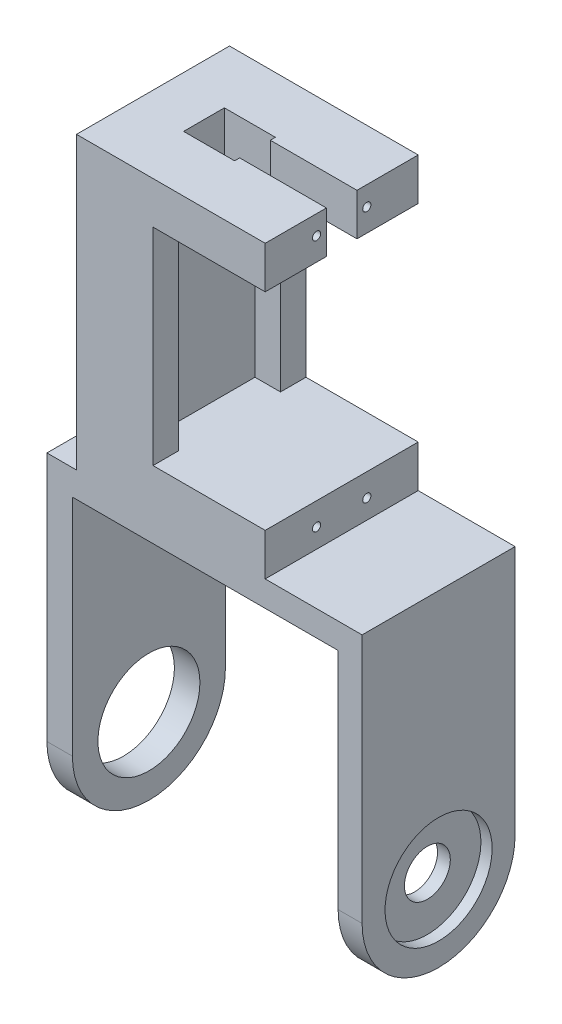
SolidWorks part; units mm, degrees
other "Marquage1"
sketch "Esquisse9" plane through (30.25, -27, 30) normal (0.9363, -0.2766, 0.2166) x (0.221, -0.0157, -0.9752)
sketch "Esquisse33" plane through (30.75, -32, 30) normal (0.9363, -0.2766, 0.2166) x (0.221, -0.0157, -0.9752)
ref_plane "Plan de face" through (0, 0, 0) normal (0, 0, 1) x (1, 0, 0)
ref_plane "Plan de dessus" through (0, 0, 0) normal (0, 1, 0) x (1, 0, 0)
ref_plane "Plan de droite" through (0, 0, 0) normal (1, 0, 0) x (0, 0, -1)
sketch "Esquisse1" plane through (0, 0, 0) normal (0, 0, 1) x (1, 0, 0)
  line L1 (-30.25, 32) -> (30.25, 32)
  line L2 (-30.25, 32) -> (-30.25, -32)
  line L3 (-30.25, -32) -> (30.25, -32)
  line L4 (30.25, 32) -> (30.25, -32)
  line L5 (-30.25, 32) -> (30.25, -32) construction
  line L6 (-30.25, -32) -> (30.25, 32) construction
  point P0 (0, 0)
  dimension "D1" = 60.5
  dimension "D2" = 64
extrude "Boss.-Extru.1" add sketch "Esquisse1" along normal blind 30
sketch "Esquisse2" plane through (30.25, 0, 0) normal (1, 0, 0) x (0, 0, -1)
  line L0 (-15, 32) -> (-15, -32) construction
  line L1 (-30, 32) -> (0, 32) construction
  line L2 (-30, -32) -> (0, -32) construction
  circle A0 centre (-15, -17) radius 4.5
  point P8 (-15, -17)
  dimension "D1" = 15
  dimension "D2" = 9
extrude "Enlèv. mat.-Extru.1" cut sketch "Esquisse2" against normal blind 32
sketch "Esquisse4" plane through (0, 0, 30) normal (0, 0, 1) x (1, 0, 0)
  line L0 (0, 0) -> (0, -11.7818) construction
  line L1 (-26.05, -56.5577) -> (26.05, -56.5577)
  line L2 (-26.05, -56.5577) -> (-26.05, 27)
  line L3 (-26.05, 27) -> (26.05, 27)
  line L4 (26.05, -56.5577) -> (26.05, 27)
  line L5 (30.25, 32) -> (-30.25, 32) construction
  line L6 (-30.25, 32) -> (-30.25, -32) construction
  dimension "D1" = 52.1
  dimension "D2" = 5
  dimension "D3" = 4.2
extrude "Enlèv. mat.-Extru.2" cut sketch "Esquisse4" against normal up to surface (30 mm away) up to face at (0, 0, 0)
sketch "Esquisse5" plane through (30.25, 0, 0) normal (1, 0, 0) x (0, 0, -1)
  circle A0 centre (-15, -17) radius 10.5
  dimension "D1" = 21
extrude "Enlèv. mat.-Extru.3" cut sketch "Esquisse5" against normal offset from surface (1.7 mm away) 2.5 up to face at (26.05, -12.5, 15)
sketch "Esquisse6" plane through (-26.05, 0, 0) normal (1, 0, 0) x (0, 0, -1)
  circle A0 centre (-15, -17) radius 10
extrude "Enlèv. mat.-Extru.4" cut sketch "Esquisse6" against normal up to surface (4.2 mm away) up to face at (-30.25, 0, 15)
sketch "Esquisse7" plane through (0, 0, 30) normal (0, 0, 1) x (1, 0, 0)
  line L0 (0, 0) -> (0, 32.5445) construction
  line L2 (-30.25, 32) -> (16.75, 32)
  line L3 (-30.25, 32) -> (-30.25, 89)
  line L4 (-30.25, 89) -> (16.75, 89)
  line L5 (16.75, 32) -> (16.75, 89)
  dimension "D1" = 57
  dimension "D2" = 47
extrude "Boss.-Extru.2" add sketch "Esquisse7" against normal up to surface (30 mm away) up to face at (0, -1.25, 0)
sketch "Esquisse8" plane through (0, 0, 30) normal (0, 0, 1) x (1, 0, 0)
  line L0 (-15.25, 90.392) -> (-15.25, 19.4965) construction
  line L1 (-30.25, 89) -> (-30.25, -32) construction
  line L2 (16.75, 60.5) -> (-55.9253, 60.5) construction
  line L3 (16.75, 32) -> (16.75, 89) construction
  line L4 (30.25, 32) -> (16.75, 32) construction
  line L6 (-15.25, 80.75) -> (11.75, 80.75)
  line L7 (-15.25, 80.75) -> (-15.25, 40.25)
  line L8 (-15.25, 40.25) -> (11.75, 40.25)
  line L10 (11.75, 40.25) -> (11.75, 32)
  line L11 (11.75, 98.5564) -> (21.75, 98.5564)
  line L12 (11.75, 98.5564) -> (11.75, 80.75)
  line L13 (11.75, 32) -> (21.75, 32)
  line L14 (21.75, 98.5564) -> (21.75, 32)
  dimension "D1" = 15
  dimension "D2" = 28.5
  dimension "D3" = 28.5
  dimension "D4" = 40.5
  dimension "D5" = 27
  dimension "D6" = 10
extrude "Enlèv. mat.-Extru.5" cut sketch "Esquisse8" against normal up to surface (30 mm away) up to face at (3.35, 16.8, 0)
sketch "Esquisse10" plane through (0, 80.75, 0) normal (0, -1, 0) x (1, 0, 0)
  line L0 (-1.75, 30) -> (-1.75, -1.0034) construction
  line L1 (-15.25, 15) -> (11.75, 15) construction
  line L2 (5.75, 0) -> (11.75, 0) construction
  line L4 (-15.25, 0) -> (11.75, 0)
  line L5 (11.75, 0) -> (11.75, 30)
  line L6 (11.75, 30) -> (-15.25, 30)
  line L7 (-15.25, 30) -> (-15.25, 0)
  line L8 (-15.25, 0) -> (-9.25, 0) construction
  line L9 (11.75, 0) -> (11.75, 30) construction
  line L10 (11.75, 30) -> (-15.25, 30) construction
  line L11 (-15.25, 30) -> (-15.25, 0) construction
  line L15 (-5.25, 11) -> (-5.25, 12)
  line L16 (-15.25, 19) -> (-5.25, 19)
  line L17 (-15.25, 19) -> (-15.25, 11)
  line L18 (-15.25, 11) -> (-5.25, 11)
  line L19 (34.75, 18) -> (34.75, 12)
  line L21 (-5.25, 19) -> (-5.25, 18)
  line L22 (-5.25, 18) -> (34.75, 18)
  line L24 (-5.25, 12) -> (34.75, 12)
  dimension "D2" = 6
  dimension "D4" = 10
  dimension "D1" = 0
extrude "Enlèv. mat.-Extru.6" cut sketch "Esquisse10" against normal up to surface (8.25 mm away) contours L17 L18 L15 L24 L19 L22 L21 L16 up to face at (-9.25, 89, 15)
sketch "Esquisse11" plane through (-15.25, 0, 0) normal (1, 0, 0) x (0, 0, -1)
  line L0 (-15, 103.0984) -> (-15, 64.9016) construction
  line L2 (0, 40.25) -> (-30, 40.25) construction
  line L3 (-30, 80.75) -> (-25, 80.75)
  line L4 (-30, 80.75) -> (-30, 40.25)
  line L5 (-30, 40.25) -> (-25, 40.25)
  line L6 (-25, 80.75) -> (-25, 40.25)
  line L7 (0, 40.25) -> (-5, 40.25)
  line L8 (-5, 80.75) -> (-5, 40.25)
  line L9 (0, 80.75) -> (-5, 80.75)
  line L10 (0, 80.75) -> (0, 40.25)
  point P3 (-15, 84)
  dimension "D1" = 5
extrude "Boss.-Extru.3" add sketch "Esquisse11" along normal blind 5
sketch "Esquisse12" plane through (11.75, 0, 0) normal (1, 0, 0) x (0, 0, -1)
  line L0 (-15, 89) -> (-15, 40.25) construction
  line L1 (-19, 89) -> (-11, 89) construction
  line L2 (0, 40.25) -> (-30, 40.25) construction
  line L3 (0, 80.75) -> (-12, 80.75) construction
  line L4 (-25, 60.5) -> (3.7732, 60.5) construction
  line L5 (-25, 40.25) -> (-25, 80.75) construction
  circle A0 centre (-19.925, 85.21) radius 0.5
  circle A1 centre (-10.075, 85.21) radius 0.5
  circle A2 centre (-10.075, 35.79) radius 0.5
  circle A3 centre (-19.925, 35.79) radius 0.5
  point P6 (-10.075, 85.21)
  point P9 (-19.925, 35.79)
  point P10 (-19.925, 85.21)
  point P15 (-10.075, 35.79)
  dimension "D3" = 1
  dimension "D1" = 4.46
  dimension "D2" = 4.925
  dimension "D4" = 4.925
  dimension "D5" = 4.46
extrude "Enlèv. mat.-Extru.7" cut sketch "Esquisse12" against normal blind 15
hole_wizard "Trou taraudé M2x0.42" positions "Esquisse3D2" profile "Esquisse14" tap size "M2x0.4" standard "Ansi Metric"
sketch3d "Esquisse3D2"
  line L0 (-3.25, 85.21, 19.925) -> (11.75, 85.21, 19.925) construction
  line L1 (-3.25, 85.21, 10.075) -> (11.75, 85.21, 10.075) construction
  line L2 (-3.25, 35.79, 10.075) -> (11.75, 35.79, 10.075) construction
  line L3 (-3.25, 35.79, 19.925) -> (11.75, 35.79, 19.925) construction
  point P0 (11.75, 85.21, 19.925)
  point P4 (11.75, 85.21, 10.075)
  point P8 (11.75, 35.79, 10.075)
  point P12 (11.75, 35.79, 19.925)
cosmetic thread "Filetage de perçage5" parameters "D1"=15, "D2"=2
cosmetic thread "Filetage de perçage6" parameters "D1"=15, "D2"=2
cosmetic thread "Filetage de perçage7" parameters "D1"=15, "D2"=2
cosmetic thread "Filetage de perçage8" parameters "D1"=15, "D2"=2
sketch "Esquisse14" plane through (11.75, 85.21, 19.925) normal (0, 1, 0) x (0, 0, -1)
  line L0 (0, 0) -> (0, 17.4807)
  line L1 (0, 17.4807) -> (0.8, 17)
  line L2 (0.8, 17) -> (0.8, 0)
  line L5 (0.8, 0) -> (0, 0)
  line L10 (0, 17.4807) -> (-0.8, 17) construction
  line L11 (0, -6.35) -> (0, 107.95) construction
  dimension "Diamètre du trou pour taraudage" = 1.6
  dimension "Profondeur du trou pour taraudage" = 17
  dimension "Angle de pointe" = 118
sketch "Esquisse15" plane through (-30.25, 0, 0) normal (-1, 0, 0) x (0, 0, 1)
  line L0 (30, -32) -> (0, -32) construction
  line L1 (40, -17) -> (30, -17)
  line L2 (0, -17) -> (-10, -17)
  arc A0 (5, -17) -> (25, -17) centre (15, -17) ccw construction
  arc A1 (0, -17) -> (30, -17) centre (15, -17) ccw
  arc A2 (-10, -17) -> (40, -17) centre (15, -17) ccw
  dimension "D1" = 20
  dimension "D2" = 50
extrude "Enlèv. mat.-Extru.8" cut sketch "Esquisse15" against normal up to surface (60.5 mm away) up to face at (30.25, -6.5, 15)
sketch "Esquisse17" plane through (-15.25, 0, 0) normal (1, 0, 0) x (0, 0, -1)
  line L0 (-15, 89) -> (-15, 40.25) construction
  line L1 (-19, 89) -> (-11, 89) construction
  line L2 (0, 40.25) -> (-30, 40.25) construction
  line L3 (-5, 70.15) -> (-34.9076, 70.15) construction
  line L4 (-5, 80.75) -> (-5, 40.25) construction
  line L5 (-25, 40.25) -> (-25, 80.75) construction
  line L6 (-5, 40.25) -> (-25, 40.25) construction
  circle A0 centre (-15, 70.15) radius 9.25
  point P14 (-15, 70.15)
  dimension "D1" = 10
  dimension "D2" = 29.9
sketch "Esquisse21" plane through (-30.25, 0, 0) normal (-1, 0, 0) x (0, 0, 1)
  circle A0 centre (15, 70.15) radius 9.25 construction
  circle A1 centre (15, 70.15) radius 9.25 construction
  circle A2 centre (15, 70.15) radius 1
  point P4 (15, 70.15)
hole_wizard "Trou taraudé M3x0.54" positions "Esquisse3D6" profile "Esquisse24" tap size "M3x0.5" standard "Ansi Metric"
sketch3d "Esquisse3D6"
  point P0 (-30.25, 70.15, 15)
sketch "Esquisse24" plane through (-30.25, 70.15, 15) normal (0, 1, 0) x (0, 0, 1)
  line L0 (0, 0) -> (0, 18.2511)
  line L1 (0, 18.2511) -> (1.25, 17.5)
  line L2 (1.25, 17.5) -> (1.25, 0)
  line L5 (1.25, 0) -> (0, 0)
  line L10 (0, 18.2511) -> (-1.25, 17.5) construction
  line L11 (0, -6.35) -> (0, 107.95) construction
  dimension "Diamètre du trou pour taraudage" = 2.5
  dimension "Profondeur du trou pour taraudage" = 17.5
  dimension "Angle de pointe" = 118
cosmetic thread "Filetage de perçage12" parameters "D1"=15, "D2"=3
sketch "Esquisse26" plane through (0, 0, 30) normal (0, 0, 1) x (1, 0, 0)
  line L0 (11.75, 32) -> (-30.25, 32) construction
  line L1 (-30.25, 89) -> (-30.25, -17) construction
  line L2 (-30.25, 96.5132) -> (-25.25, 96.5132)
  line L3 (-30.25, 96.5132) -> (-30.25, 32)
  line L4 (-30.25, 32) -> (-25.25, 32)
  line L5 (-25.25, 96.5132) -> (-25.25, 32)
  dimension "D1" = 5
extrude "Enlèv. mat.-Extru.9" cut sketch "Esquisse26" against normal up to surface (30 mm away) up to face at (1.8929, 33.5714, 0)
sketch "Esquisse27" plane through (-30.25, 0, 0) normal (-1, 0, 0) x (0, 0, 1)
  line L3 (30, -17) -> (30, 32)
  line L4 (30, 32) -> (0, 32)
  line L5 (0, 32) -> (0, -17)
  line L6 (30, -17) -> (30, 32)
  line L7 (30, 32) -> (0, 32)
  line L8 (0, 32) -> (0, -17)
  arc A1 (0, -17) -> (30, -17) centre (15, -17) ccw
  arc A2 (0, -17) -> (30, -17) centre (15, -17) ccw
  dimension "D1" = 0
extrude "Boss.-Extru.5" add sketch "Esquisse27" along normal blind 0.8
sketch "Esquisse28" plane through (30.25, 0, 0) normal (1, 0, 0) x (0, 0, -1)
  line L3 (-30, 32) -> (-30, -17)
  line L4 (0, -17) -> (0, 32)
  line L5 (0, 32) -> (-30, 32)
  line L6 (-30, 32) -> (-30, -17)
  line L7 (0, -17) -> (0, 32)
  line L8 (0, 32) -> (-30, 32)
  arc A1 (-30, -17) -> (0, -17) centre (-15, -17) ccw
  arc A2 (-30, -17) -> (0, -17) centre (-15, -17) ccw
  dimension "D1" = 0
extrude "Boss.-Extru.6" add sketch "Esquisse28" along normal blind 0.5
sketch "Esquisse30" plane through (-30.25, 0, 0) normal (1, 0, 0) x (0, 0, -1)
  circle A1 centre (-15, -17) radius 10
  circle A2 centre (-15, -17) radius 10
  dimension "D1" = 0
extrude "Enlèv. mat.-Extru.10" cut sketch "Esquisse30" against normal blind 20.5
sketch "Esquisse32" plane through (30.25, 0, 0) normal (-1, 0, 0) x (0, 0, 1)
  circle A1 centre (15, -17) radius 10.5
  circle A2 centre (15, -17) radius 10.5
  dimension "D1" = 0
extrude "Enlèv. mat.-Extru.13" cut sketch "Esquisse32" against normal blind 20.5
